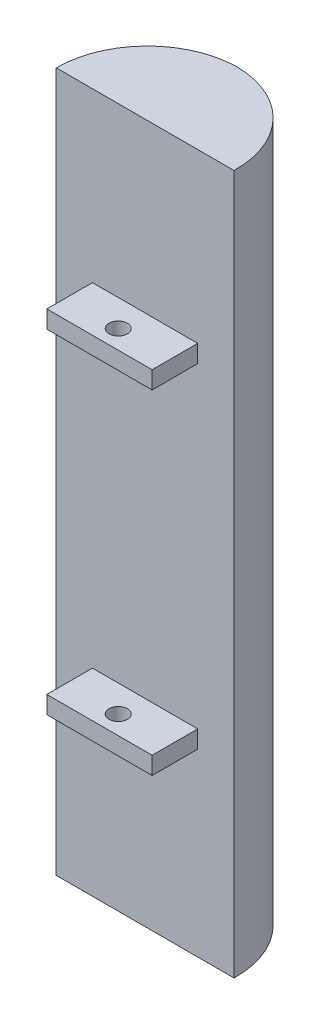
SolidWorks part; units mm, degrees
ref_plane "Front Plane" through (0, 0, 0) normal (0, 0, 1) x (1, 0, 0)
ref_plane "Top Plane" through (0, 0, 0) normal (0, 1, 0) x (1, 0, 0)
ref_plane "Right Plane" through (0, 0, 0) normal (1, 0, 0) x (0, 0, -1)
sketch "Sketch1" plane through (0, 0, 0) normal (0, 1, 0) x (1, 0, 0)
  line L0 (-76, 0) -> (76, 0)
  arc A0 (-76, 0) -> (0, 78) centre (2.0263, 0) cw
  arc A1 (0, 78) -> (76, 0) centre (0, 1.9744) cw
  point P4 (0, 0)
extrude "Boss-Extrude1" add sketch "Sketch1" along normal blind 598
sketch "Sketch2" plane through (0, 0, 0) normal (0, 0, 1) x (1, 0, 0)
  line L3 (-45, 439.4402) -> (45, 439.4402)
  line L4 (-45, 439.4402) -> (-45, 454.4402)
  line L5 (-45, 454.4402) -> (45, 454.4402)
  line L6 (45, 439.4402) -> (45, 454.4402)
  line L7 (-45, 439.4402) -> (45, 454.4402) construction
  line L8 (-45, 454.4402) -> (45, 439.4402) construction
  line L9 (-45, 153.9605) -> (45, 153.9605)
  line L10 (-45, 153.9605) -> (-45, 168.9605)
  line L11 (-45, 168.9605) -> (45, 168.9605)
  line L12 (45, 153.9605) -> (45, 168.9605)
  line L13 (-45, 153.9605) -> (45, 168.9605) construction
  line L14 (-45, 168.9605) -> (45, 153.9605) construction
  point P5 (0, 446.9402)
  point P10 (0, 161.4605)
  dimension "D1" = 15
  dimension "D2" = 90
  dimension "D3" = 15
  dimension "D4" = 90
extrude "Boss-Extrude2" add sketch "Sketch2" along normal blind 39
sketch "Sketch3" plane through (0, 153.9605, 0) normal (0, -1, 0) x (-1, 0, 0)
  circle A0 centre (0, -22.9839) radius 7.875
  dimension "D1" = 15.75
extrude "Cut-Extrude1" cut sketch "Sketch3" against normal through all both and the other way through all
